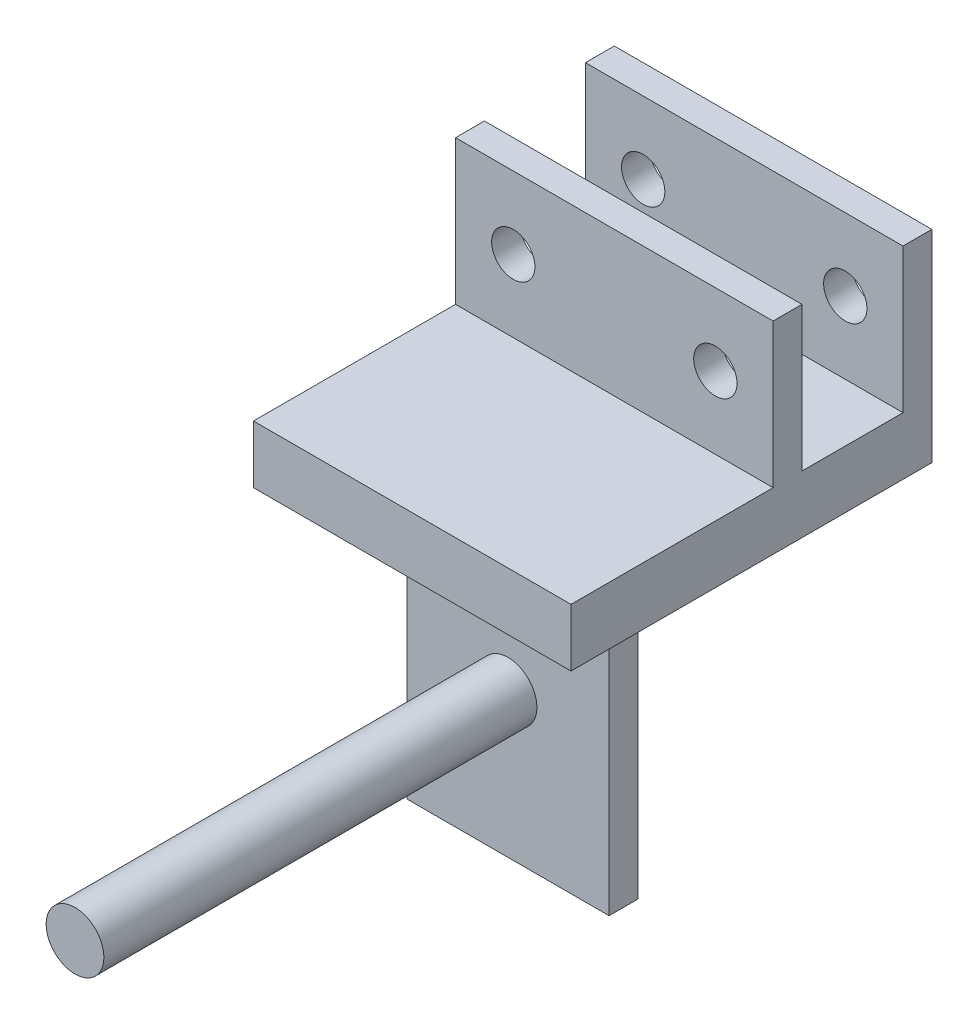
SolidWorks part; units mm, degrees
ref_plane "Спереди" through (0, 0, 0) normal (0, 0, 1) x (1, 0, 0)
ref_plane "Сверху" through (0, 0, 0) normal (0, 1, 0) x (1, 0, 0)
ref_plane "Справа" through (0, 0, 0) normal (1, 0, 0) x (0, 0, -1)
sketch "Эскиз2" plane through (0, 0, 0) normal (0, 1, 0) x (1, 0, 0)
  line L1 (-45.832, -5.4416) -> (-23.832, -5.4416)
  line L2 (-45.832, -5.4416) -> (-45.832, -30.4416)
  line L3 (-45.832, -30.4416) -> (-23.832, -30.4416)
  line L4 (-23.832, -5.4416) -> (-23.832, -30.4416)
extrude "Бобышка-Вытянуть1" add sketch "Эскиз2" along normal blind 4
sketch "Эскиз3" plane through (0, 4, 0) normal (0, 1, 0) x (1, 0, 0)
  line L0 (-23.832, -30.4416) -> (-23.832, -5.4416) construction
  line L1 (-45.832, -5.4416) -> (-23.832, -5.4416)
  line L2 (-45.832, -5.4416) -> (-45.832, -7.4416)
  line L3 (-45.832, -7.4416) -> (-23.832, -7.4416)
  line L4 (-23.832, -5.4416) -> (-23.832, -7.4416)
  line L5 (-45.832, -14.4416) -> (-23.832, -14.4416)
  line L6 (-45.832, -5.4416) -> (-45.832, -30.4416) construction
  line L7 (-45.832, -16.4416) -> (-23.832, -16.4416)
  line M4 (-45.832, -5.4416) -> (-45.832, -30.4416)
  line M6 (-23.832, -30.4416) -> (-23.832, -5.4416)
  line M7 (-23.832, -5.4416) -> (-45.832, -5.4416)
  dimension "D1" = 7
  dimension "D2" = 2
  dimension "D3" = 2
extrude "Бобышка-Вытянуть2" add sketch "Эскиз3" along normal blind 10 contours L3 M4 M6 M7 | L7 L5 M4 M6
sketch "Эскиз4" plane through (0, 0, 16.4416) normal (0, 0, 1) x (1, 0, 0)
  line L0 (-34.832, 4) -> (-34.832, 14) construction
  line L1 (-45.832, 4) -> (-23.832, 4) construction
  line L2 (-45.832, 14) -> (-23.832, 14) construction
  line L3 (-45.832, 9) -> (-23.832, 9) construction
  line L4 (-45.832, 14) -> (-45.832, 4) construction
  line L5 (-23.832, 14) -> (-23.832, 4) construction
  line L6 (-41.832, 14) -> (-41.832, 4) construction
  line L7 (-45.832, 4) -> (-23.832, 4) construction
  line L8 (-27.832, 14) -> (-27.832, 4) construction
  circle A0 centre (-41.832, 9) radius 1.5
  circle A1 centre (-27.832, 9) radius 1.5
  dimension "D1" = 5
  dimension "D2" = 7
  dimension "D3" = 7
extrude "Вырез-Вытянуть1" cut sketch "Эскиз4" against normal blind 11
sketch "Эскиз5" plane through (0, 0, 0) normal (0, -1, 0) x (1, 0, 0)
  line L0 (-34.832, 30.4416) -> (-34.832, 5.4416) construction
  line L1 (-45.832, 30.4416) -> (-23.832, 30.4416) construction
  line L2 (-23.832, 5.4416) -> (-45.832, 5.4416) construction
  line L4 (-41.832, 23.8053) -> (-27.832, 23.8053)
  line L5 (-41.832, 23.8053) -> (-41.832, 21.8053)
  line L6 (-41.832, 21.8053) -> (-27.832, 21.8053)
  line L7 (-27.832, 23.8053) -> (-27.832, 21.8053)
  dimension "D1" = 7
  dimension "D2" = 7
  dimension "D3" = 2
extrude "Бобышка-Вытянуть3" add sketch "Эскиз5" along normal blind 20
sketch "Эскиз6" plane through (0, 0, 23.8053) normal (0, 0, 1) x (1, 0, 0)
  line L0 (-34.832, 0) -> (-34.832, -20) construction
  line L1 (-27.832, 0) -> (-41.832, 0) construction
  line L2 (-27.832, -20) -> (-41.832, -20) construction
  line L3 (-41.832, -10) -> (-27.832, -10) construction
  line L4 (-41.832, -20) -> (-41.832, 0) construction
  line L5 (-27.832, -20) -> (-27.832, 0) construction
  circle A0 centre (-34.832, -10) radius 2
  dimension "D1" = 10
extrude "Бобышка-Вытянуть4" add sketch "Эскиз6" along normal blind 30
